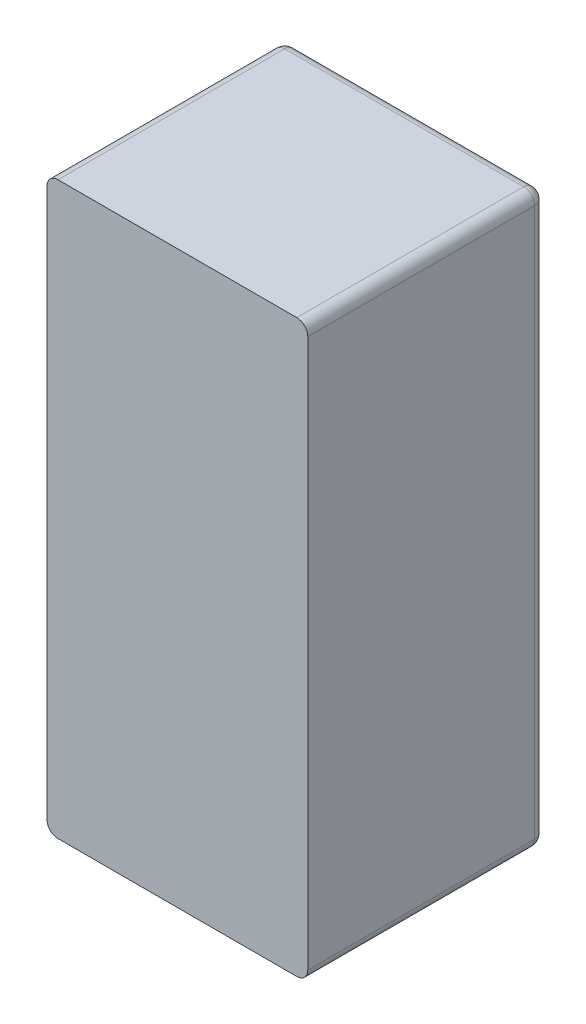
SolidWorks part; units mm, degrees
ref_plane "Front Plane" through (0, 0, 0) normal (0, 0, 1) x (1, 0, 0)
ref_plane "Top Plane" through (0, 0, 0) normal (0, 1, 0) x (1, 0, 0)
ref_plane "Right Plane" through (0, 0, 0) normal (1, 0, 0) x (0, 0, -1)
sketch "Sketch1" plane through (0, 0, 0) normal (0, 1, 0) x (1, 0, 0)
  line L1 (0, 0) -> (-237.998, 0)
  line L2 (0, 0) -> (0, -216.916)
  line L3 (0, -216.916) -> (-237.998, -216.916)
  line L4 (-237.998, 0) -> (-237.998, -216.916)
  dimension "D1" = 216.916
  dimension "D2" = 237.998
extrude "Boss-Extrude1" add sketch "Sketch1" along normal blind 520.7
fillet "Fillet1" radius 10 8 edges at (0, 260.35, 0) (-118.999, 520.7, 0) (-237.998, 260.35, 0) (-118.999, 0, 0) (-237.998, 520.7, 108.458) (-237.998, 0, 108.458) (0, 520.7, 108.458) (0, 0, 108.458)
